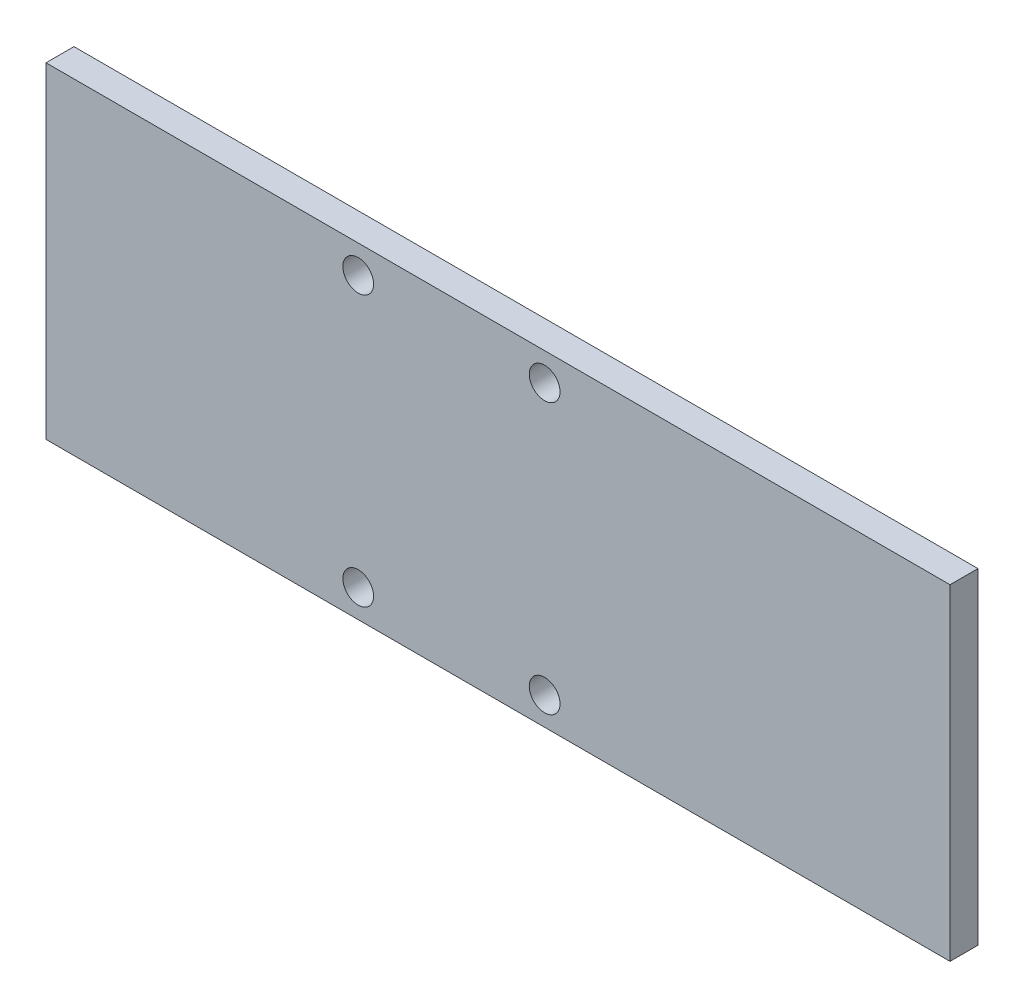
SolidWorks part; units mm, degrees
ref_plane "前视基准面" through (0, 0, 0) normal (0, 0, 1) x (1, 0, 0)
ref_plane "上视基准面" through (0, 0, 0) normal (0, 1, 0) x (1, 0, 0)
ref_plane "右视基准面" through (0, 0, 0) normal (1, 0, 0) x (0, 0, -1)
other "Configuration Table"
sketch "草图1" plane through (0, 0, 0) normal (0, 0, 1) x (1, 0, 0)
  line L1 (-48.5, -17.5) -> (48.5, -17.5)
  line L2 (-48.5, -17.5) -> (-48.5, 17.5)
  line L3 (-48.5, 17.5) -> (48.5, 17.5)
  line L4 (48.5, -17.5) -> (48.5, 17.5)
  line L5 (-48.5, -17.5) -> (48.5, 17.5) construction
  line L6 (-48.5, 17.5) -> (48.5, -17.5) construction
  point P0 (0, 0)
  dimension "D1" = 35
  dimension "D2" = 97
extrude "凸台-拉伸1" add sketch "草图1" along normal blind 3
sketch "草图2" plane through (0, 0, 0) normal (0, 0, -1) x (-1, 0, 0)
  circle A0 centre (-5, -14.5) radius 1.65 construction
  circle A1 centre (15, -14.5) radius 1.65 construction
  circle A2 centre (-5, -14.5) radius 1.65
  circle A3 centre (15, -14.5) radius 1.65
  circle A4 centre (-5, 14.5) radius 1.65 construction
  circle A5 centre (15, 14.5) radius 1.65 construction
  circle A6 centre (-5, 14.5) radius 1.65
  circle A7 centre (15, 14.5) radius 1.65
extrude "切除-拉伸1" cut sketch "草图2" against normal blind 3
